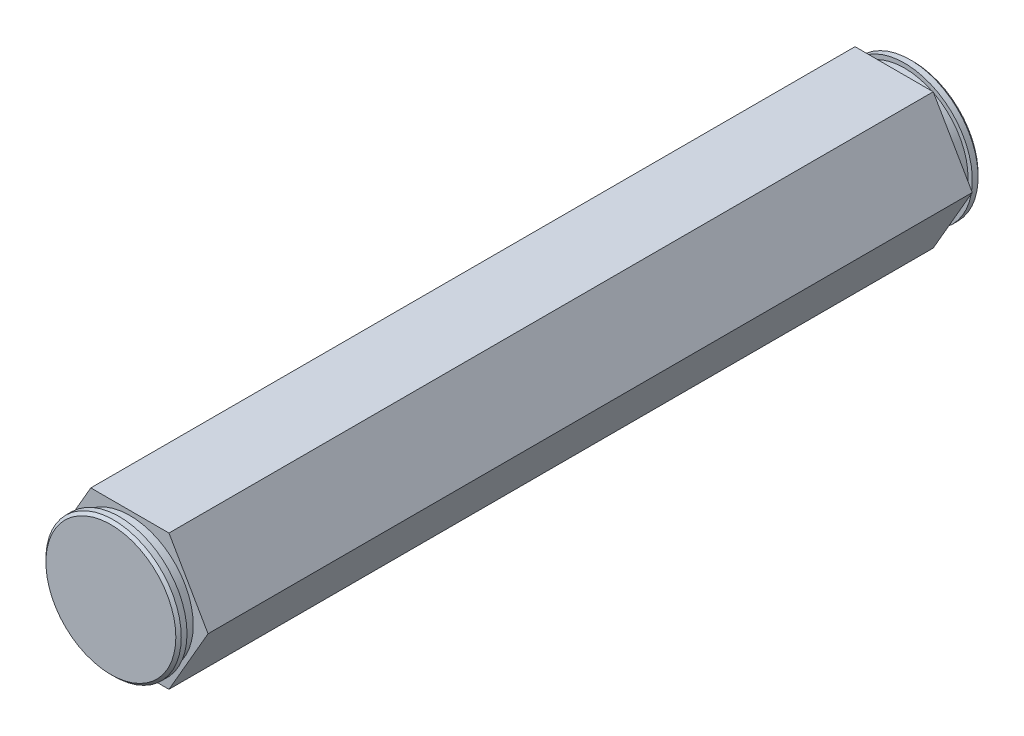
SolidWorks part; units mm, degrees
ref_plane "Front Plane" through (0, 0, 0) normal (0, 0, 1) x (1, 0, 0)
ref_plane "Top Plane" through (0, 0, 0) normal (0, 1, 0) x (1, 0, 0)
ref_plane "Right Plane" through (0, 0, 0) normal (1, 0, 0) x (0, 0, -1)
sketch "Sketch1" plane through (0, 0, 0) normal (0, 0, 1) x (1, 0, 0)
  line L1 (7.3323, 0) -> (3.6662, 6.35)
  line L2 (3.6662, 6.35) -> (-3.6662, 6.35)
  line L3 (-3.6662, 6.35) -> (-7.3323, 0)
  line L4 (-7.3323, 0) -> (-3.6662, -6.35)
  line L5 (-3.6662, -6.35) -> (3.6662, -6.35)
  line L6 (3.6662, -6.35) -> (7.3323, 0)
  circle A0 centre (0, 0) radius 6.35 construction
  dimension "D1" = 12.7
extrude "Boss-Extrude1" add sketch "Sketch1" along normal mid plane 28.575
sketch "Sketch2" plane through (0, 0, -14.2875) normal (0, 0, -1) x (-1, 0, 0)
  circle A0 centre (0, 0) radius 5.9436
  dimension "D1" = 11.8872
extrude "Boss-Extrude2" add sketch "Sketch2" along normal blind 0.9906
sketch "Sketch3" plane through (0, 0, -15.2781) normal (0, 0, -1) x (-1, 0, 0)
  circle A0 centre (0, 0) radius 6.35
  dimension "D1" = 12.7
extrude "Boss-Extrude3" add sketch "Sketch3" along normal blind 0.7937
chamfer "Chamfer1" distance 0.254 angle 45 1 edges at (-6.35, 0, -16.0718)
sketch "Sketch4" plane through (0, 0, -16.0718) normal (0, 0, -1) x (-1, 0, 0)
  circle A0 centre (0, 0) radius 3.175
  dimension "D1" = 6.35
extrude "Cut-Extrude1" cut sketch "Sketch4" against normal blind 12.7
sketch "Sketch5" plane through (0, 0, 14.2875) normal (0, 0, 1) x (1, 0, 0)
  line L1 (3.6662, 6.35) -> (-3.6662, 6.35)
  line L2 (-3.6662, 6.35) -> (-7.3323, 0)
  line L3 (-7.3323, 0) -> (-3.6662, -6.35)
  line L4 (-3.6662, -6.35) -> (3.6662, -6.35)
  line L5 (3.6662, -6.35) -> (7.3323, 0)
  line L6 (7.3323, 0) -> (3.6662, 6.35)
  circle A0 centre (0, 0) radius 6.35 construction
  dimension "D1" = 12.7
extrude "Boss-Extrude4" add sketch "Sketch5" along normal blind 43.1165
sketch "Sketch6" plane through (0, 0, 57.404) normal (0, 0, 1) x (1, 0, 0)
  circle A0 centre (0, 0) radius 5.9436
  dimension "D1" = 11.8872
extrude "Boss-Extrude5" add sketch "Sketch6" along normal blind 0.9906
sketch "Sketch7" plane through (0, 0, 58.3946) normal (0, 0, 1) x (1, 0, 0)
  circle A0 centre (0, 0) radius 6.35
  dimension "D1" = 12.7
extrude "Boss-Extrude6" add sketch "Sketch7" along normal blind 0.7937
chamfer "Chamfer2" distance 0.254 angle 45 1 edges at (6.35, 0, 59.1884)
